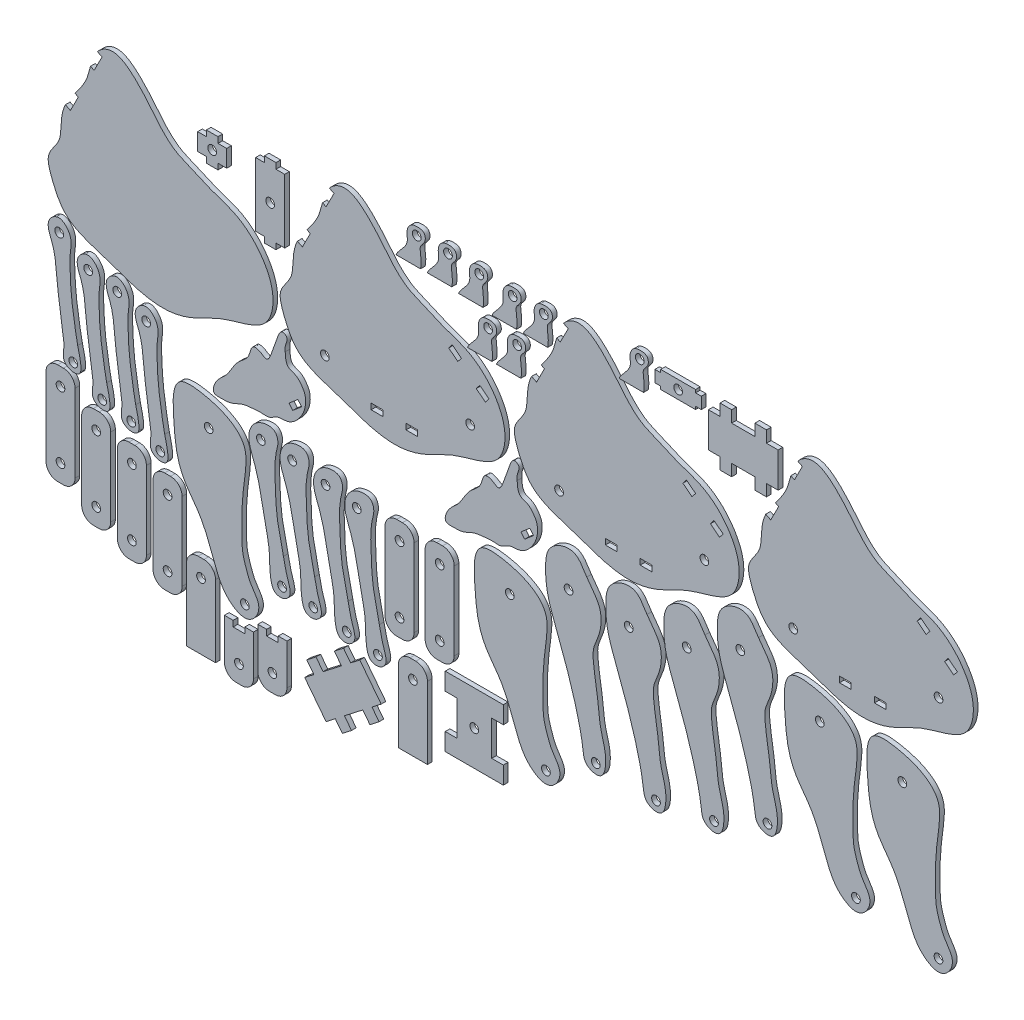
SolidWorks part; units mm, degrees
ref_plane "Front Plane" through (0, 0, 0) normal (0, 0, 1) x (1, 0, 0)
ref_plane "Top Plane" through (0, 0, 0) normal (0, 1, 0) x (1, 0, 0)
ref_plane "Right Plane" through (0, 0, 0) normal (1, 0, 0) x (0, 0, -1)
sketch "Model" plane through (0, 0, 0) normal (0, 0, 1) x (1, 0, 0)
  line L0 (104.0914, 221.0208) -> (99.0726, 224.9111)
  line L1 (99.0726, 224.9111) -> (101.0177, 227.4205)
  line L2 (101.0177, 227.4205) -> (106.0365, 223.5302)
  line L3 (106.0365, 223.5302) -> (104.0914, 221.0208)
  line L4 (116.0741, 215.7496) -> (121.0928, 211.8593)
  line L5 (121.0928, 211.8593) -> (119.1477, 209.3499)
  line L6 (119.1477, 209.3499) -> (114.1289, 213.2402)
  line L7 (114.1289, 213.2402) -> (116.0741, 215.7496)
  line L8 (63.047, 177.6396) -> (56.697, 177.6396)
  line L9 (63.047, 174.4646) -> (63.047, 177.6396)
  line L10 (63.047, 174.4646) -> (56.697, 174.4646)
  line L11 (56.697, 174.4646) -> (56.697, 177.6396)
  line L12 (82.097, 177.6396) -> (75.747, 177.6396)
  line L13 (82.097, 174.4646) -> (82.097, 177.6396)
  line L14 (82.097, 174.4646) -> (75.747, 174.4646)
  line L15 (75.747, 174.4646) -> (75.747, 177.6396)
  line L16 (23.4135, 241.2367) -> (21.6354, 242.1418)
  line L17 (19.0926, 232.7482) -> (23.4135, 241.2367)
  line L18 (19.0926, 232.7482) -> (16.3784, 234.1298)
  line L19 (36.3762, 266.7024) -> (33.8655, 267.9804)
  line L20 (32.0553, 258.2138) -> (36.3762, 266.7024)
  line L21 (32.0553, 258.2138) -> (30.1044, 259.2069)
  line L22 (230.8793, 219.8022) -> (225.8605, 223.6925)
  line L23 (225.8605, 223.6925) -> (227.8057, 226.2019)
  line L24 (227.8057, 226.2019) -> (232.8244, 222.3116)
  line L25 (232.8244, 222.3116) -> (230.8793, 219.8022)
  line L26 (242.862, 214.531) -> (247.8808, 210.6408)
  line L27 (247.8808, 210.6408) -> (245.9356, 208.1314)
  line L28 (245.9356, 208.1314) -> (240.9168, 212.0217)
  line L29 (240.9168, 212.0217) -> (242.862, 214.531)
  line L30 (189.8349, 176.421) -> (183.4849, 176.421)
  line L31 (189.8349, 173.246) -> (189.8349, 176.421)
  line L32 (189.8349, 173.246) -> (183.4849, 173.246)
  line L33 (183.4849, 173.246) -> (183.4849, 176.421)
  line L34 (208.8849, 176.421) -> (202.5349, 176.421)
  line L35 (208.8849, 173.246) -> (208.8849, 176.421)
  line L36 (208.8849, 173.246) -> (202.5349, 173.246)
  line L37 (202.5349, 173.246) -> (202.5349, 176.421)
  line L38 (150.2014, 240.0182) -> (148.4234, 240.9232)
  line L39 (145.8805, 231.5296) -> (150.2014, 240.0182)
  line L40 (145.8805, 231.5296) -> (143.1663, 232.9112)
  line L41 (163.1641, 265.4838) -> (160.6534, 266.7618)
  line L42 (158.8432, 256.9953) -> (163.1641, 265.4838)
  line L43 (158.8432, 256.9953) -> (156.8923, 257.9883)
  line L44 (358.8863, 219.8022) -> (353.8676, 223.6925)
  line L45 (353.8676, 223.6925) -> (355.8127, 226.2019)
  line L46 (355.8127, 226.2019) -> (360.8315, 222.3116)
  line L47 (360.8315, 222.3116) -> (358.8863, 219.8022)
  line L48 (370.869, 214.531) -> (375.8878, 210.6408)
  line L49 (375.8878, 210.6408) -> (373.9427, 208.1314)
  line L50 (373.9427, 208.1314) -> (368.9239, 212.0217)
  line L51 (368.9239, 212.0217) -> (370.869, 214.531)
  line L52 (317.842, 176.421) -> (311.492, 176.421)
  line L53 (317.842, 173.246) -> (317.842, 176.421)
  line L54 (317.842, 173.246) -> (311.492, 173.246)
  line L55 (311.492, 173.246) -> (311.492, 176.421)
  line L56 (336.892, 176.421) -> (330.542, 176.421)
  line L57 (336.892, 173.246) -> (336.892, 176.421)
  line L58 (336.892, 173.246) -> (330.542, 173.246)
  line L59 (330.542, 173.246) -> (330.542, 176.421)
  line L60 (278.2085, 240.0182) -> (276.4304, 240.9232)
  line L61 (273.8876, 231.5296) -> (278.2085, 240.0182)
  line L62 (273.8876, 231.5296) -> (271.1734, 232.9112)
  line L63 (291.1712, 265.4838) -> (288.6604, 266.7618)
  line L64 (286.8503, 256.9953) -> (291.1712, 265.4838)
  line L65 (286.8503, 256.9953) -> (284.8994, 257.9883)
  line L66 (486.8934, 218.5837) -> (481.8746, 222.474)
  line L67 (481.8746, 222.474) -> (483.8198, 224.9833)
  line L68 (483.8198, 224.9833) -> (488.8385, 221.0931)
  line L69 (488.8385, 221.0931) -> (486.8934, 218.5837)
  line L70 (498.8761, 213.3125) -> (503.8949, 209.4222)
  line L71 (503.8949, 209.4222) -> (501.9497, 206.9128)
  line L72 (501.9497, 206.9128) -> (496.9309, 210.8031)
  line L73 (496.9309, 210.8031) -> (498.8761, 213.3125)
  line L74 (445.849, 175.2024) -> (439.499, 175.2024)
  line L75 (445.849, 172.0274) -> (445.849, 175.2024)
  line L76 (445.849, 172.0274) -> (439.499, 172.0274)
  line L77 (439.499, 172.0274) -> (439.499, 175.2024)
  line L78 (464.899, 175.2024) -> (458.549, 175.2024)
  line L79 (464.899, 172.0274) -> (464.899, 175.2024)
  line L80 (464.899, 172.0274) -> (458.549, 172.0274)
  line L81 (458.549, 172.0274) -> (458.549, 175.2024)
  line L82 (406.2155, 238.7996) -> (404.4375, 239.7046)
  line L83 (401.8946, 230.311) -> (406.2155, 238.7996)
  line L84 (401.8946, 230.311) -> (399.1804, 231.6926)
  line L85 (419.1782, 264.2652) -> (416.6675, 265.5432)
  line L86 (414.8573, 255.7767) -> (419.1782, 264.2652)
  line L87 (414.8573, 255.7767) -> (412.9064, 256.7697)
  line L88 (393.2253, 240.0541) -> (399.5753, 240.0541)
  line L89 (399.5753, 246.4041) -> (399.5753, 240.0541)
  line L90 (405.9253, 246.4041) -> (399.5753, 246.4041)
  line L91 (405.9253, 265.4541) -> (405.9253, 246.4041)
  line L92 (399.5753, 265.4541) -> (405.9253, 265.4541)
  line L93 (399.5753, 271.8041) -> (399.5753, 265.4541)
  line L94 (393.2253, 271.8041) -> (399.5753, 271.8041)
  line L95 (393.2253, 265.4541) -> (393.2253, 271.8041)
  line L96 (380.5253, 265.4541) -> (393.2253, 265.4541)
  line L97 (380.5253, 271.8041) -> (380.5253, 265.4541)
  line L98 (374.1753, 271.8041) -> (380.5253, 271.8041)
  line L99 (374.1753, 265.4541) -> (374.1753, 271.8041)
  line L100 (367.8253, 265.4541) -> (374.1753, 265.4541)
  line L101 (367.8253, 265.4541) -> (367.8253, 246.4041)
  line L102 (374.1753, 246.4041) -> (367.8253, 246.4041)
  line L103 (374.1753, 240.0541) -> (374.1753, 246.4041)
  line L104 (374.1753, 240.0541) -> (380.5253, 240.0541)
  line L105 (380.5253, 246.4041) -> (380.5253, 240.0541)
  line L106 (393.2253, 246.4041) -> (380.5253, 246.4041)
  line L107 (393.2253, 240.0541) -> (393.2253, 246.4041)
  line L108 (140.6345, 151.5366) -> (145.4631, 155.6606)
  line L109 (140.6345, 151.5366) -> (138.5725, 153.9509)
  line L110 (138.5725, 153.9509) -> (143.4011, 158.0749)
  line L111 (145.4631, 155.6606) -> (143.4011, 158.0749)
  line L112 (267.4224, 153.9738) -> (272.251, 158.0978)
  line L113 (267.4224, 153.9738) -> (265.3604, 156.3881)
  line L114 (265.3604, 156.3881) -> (270.189, 160.5121)
  line L115 (272.251, 158.0978) -> (270.189, 160.5121)
  line L116 (341.7415, 269.9261) -> (338.5665, 269.9261)
  line L117 (338.5665, 269.9261) -> (338.5665, 263.5761)
  line L118 (341.7415, 263.5761) -> (338.5665, 263.5761)
  line L119 (341.7415, 261.9886) -> (341.7415, 263.5761)
  line L120 (360.7915, 261.9886) -> (341.7415, 261.9886)
  line L121 (360.7915, 261.9886) -> (360.7915, 263.5761)
  line L122 (360.7915, 263.5761) -> (363.9665, 263.5761)
  line L123 (363.9665, 263.5761) -> (363.9665, 269.9261)
  line L124 (360.7915, 269.9261) -> (363.9665, 269.9261)
  line L125 (360.7915, 269.9261) -> (360.7915, 271.5136)
  line L126 (360.7915, 271.5136) -> (341.7415, 271.5136)
  line L127 (341.7415, 269.9261) -> (341.7415, 271.5136)
  line L128 (197.1492, 253.4585) -> (210.4597, 253.4585)
  line L129 (214.2168, 253.4585) -> (227.5273, 253.4585)
  line L130 (231.2844, 252.2399) -> (244.5949, 252.2399)
  line L131 (249.5712, 251.0213) -> (262.8816, 251.0213)
  line L132 (266.6388, 251.0213) -> (279.9492, 251.0213)
  line L133 (252.0094, 229.0869) -> (265.3199, 229.0869)
  line L134 (236.1609, 229.0869) -> (249.4714, 229.0869)
  line L135 (319.0607, 255.8957) -> (332.3712, 255.8957)
  line L136 (120.345, 226.169) -> (120.345, 261.094)
  line L137 (125.1075, 226.169) -> (120.345, 226.169)
  line L138 (125.1075, 226.169) -> (125.1075, 222.994)
  line L139 (125.1075, 222.994) -> (131.4575, 222.994)
  line L140 (131.4575, 226.169) -> (131.4575, 222.994)
  line L141 (136.22, 226.169) -> (131.4575, 226.169)
  line L142 (136.22, 226.169) -> (136.22, 261.094)
  line L143 (136.22, 261.094) -> (131.4575, 261.094)
  line L144 (131.4575, 261.094) -> (131.4575, 264.269)
  line L145 (125.1075, 264.269) -> (131.4575, 264.269)
  line L146 (125.1075, 261.094) -> (125.1075, 264.269)
  line L147 (125.1075, 261.094) -> (120.345, 261.094)
  line L148 (12.0982, 53.6112) -> (15.2732, 53.6112)
  line L149 (21.6232, 59.9612) -> (21.6232, 102.5062)
  line L150 (15.2732, 108.8562) -> (12.0982, 108.8562)
  line L151 (5.7482, 102.5062) -> (5.7482, 59.9612)
  line L152 (31.604, 42.6439) -> (34.779, 42.6439)
  line L153 (41.129, 48.9939) -> (41.129, 91.5389)
  line L154 (34.779, 97.8889) -> (31.604, 97.8889)
  line L155 (25.254, 91.5389) -> (25.254, 48.9939)
  line L156 (51.1099, 36.551) -> (54.2849, 36.551)
  line L157 (60.6349, 42.901) -> (60.6349, 85.446)
  line L158 (54.2849, 91.796) -> (51.1099, 91.796)
  line L159 (44.7599, 85.446) -> (44.7599, 42.901)
  line L160 (70.6157, 31.6767) -> (73.7907, 31.6767)
  line L161 (80.1407, 38.0267) -> (80.1407, 80.5717)
  line L162 (73.7907, 86.9217) -> (70.6157, 86.9217)
  line L163 (64.2657, 80.5717) -> (64.2657, 38.0267)
  line L164 (197.4036, 73.1085) -> (200.5786, 73.1085)
  line L165 (206.9286, 79.4585) -> (206.9286, 122.0035)
  line L166 (200.5786, 128.3535) -> (197.4036, 128.3535)
  line L167 (191.0536, 122.0035) -> (191.0536, 79.4585)
  line L168 (219.3477, 73.1085) -> (222.5227, 73.1085)
  line L169 (228.8727, 79.4585) -> (228.8727, 122.0035)
  line L170 (222.5227, 128.3535) -> (219.3477, 128.3535)
  line L171 (212.9977, 122.0035) -> (212.9977, 79.4585)
  line L172 (223.9697, 60.2517) -> (223.9697, 69.7767)
  line L173 (230.3197, 60.2517) -> (223.9697, 60.2517)
  line L174 (230.3197, 41.2017) -> (230.3197, 60.2517)
  line L175 (230.3197, 41.2017) -> (223.9697, 41.2017)
  line L176 (223.9697, 31.6767) -> (223.9697, 41.2017)
  line L177 (223.9697, 31.6767) -> (255.7197, 31.6767)
  line L178 (255.7197, 31.6767) -> (255.7197, 41.2017)
  line L179 (249.3697, 41.2017) -> (255.7197, 41.2017)
  line L180 (249.3697, 41.2017) -> (249.3697, 60.2517)
  line L181 (249.3697, 60.2517) -> (255.7197, 60.2517)
  line L182 (255.7197, 69.7767) -> (255.7197, 60.2517)
  line L183 (255.7197, 69.7767) -> (223.9697, 69.7767)
  line L184 (82.5524, 10.9608) -> (82.5524, 50.3308)
  line L185 (82.5524, 10.9608) -> (98.4274, 10.9608)
  line L186 (98.4274, 10.9608) -> (98.4274, 50.3308)
  line L187 (88.9024, 56.6808) -> (92.0774, 56.6808)
  line L188 (198.3683, 20.7095) -> (198.3683, 60.0795)
  line L189 (198.3683, 20.7095) -> (214.2433, 20.7095)
  line L190 (214.2433, 20.7095) -> (214.2433, 60.0795)
  line L191 (204.7183, 66.4295) -> (207.8933, 66.4295)
  line L192 (108.0399, 32.7051) -> (108.0399, 35.8801)
  line L193 (108.0399, 35.8801) -> (103.2774, 35.8801)
  line L194 (103.2774, 35.8801) -> (103.2774, 13.6551)
  line L195 (109.6274, 7.3051) -> (112.8024, 7.3051)
  line L196 (119.1524, 13.6551) -> (119.1524, 35.8801)
  line L197 (119.1524, 35.8801) -> (114.3899, 35.8801)
  line L198 (114.3899, 35.8801) -> (114.3899, 32.7051)
  line L199 (114.3899, 32.7051) -> (108.0399, 32.7051)
  line L200 (126.3266, 37.5794) -> (126.3266, 40.7544)
  line L201 (126.3266, 40.7544) -> (121.5641, 40.7544)
  line L202 (121.5641, 40.7544) -> (121.5641, 18.5294)
  line L203 (127.9141, 12.1794) -> (131.0891, 12.1794)
  line L204 (137.4391, 18.5294) -> (137.4391, 40.7544)
  line L205 (137.4391, 40.7544) -> (132.6766, 40.7544)
  line L206 (132.6766, 40.7544) -> (132.6766, 37.5794)
  line L207 (132.6766, 37.5794) -> (126.3266, 37.5794)
  line L208 (88.648, 248.1034) -> (93.4105, 248.1034)
  line L209 (93.4105, 248.1034) -> (93.4105, 244.9284)
  line L210 (93.4105, 244.9284) -> (99.7605, 244.9284)
  line L211 (99.7605, 248.1034) -> (99.7605, 244.9284)
  line L212 (99.7605, 248.1034) -> (104.523, 248.1034)
  line L213 (104.523, 248.1034) -> (104.523, 257.5014)
  line L214 (99.7605, 257.5014) -> (104.523, 257.5014)
  line L215 (99.7605, 257.5014) -> (99.7605, 260.6764)
  line L216 (93.4105, 260.6764) -> (99.7605, 260.6764)
  line L217 (93.4105, 257.5014) -> (93.4105, 260.6764)
  line L218 (88.648, 257.5014) -> (93.4105, 257.5014)
  line L219 (88.648, 248.1034) -> (88.648, 257.5014)
  line L220 (182.8018, 23.8503) -> (187.8206, 27.7406)
  line L221 (183.9303, 32.7594) -> (187.8206, 27.7406)
  line L222 (188.9491, 36.6496) -> (183.9303, 32.7594)
  line L223 (177.2782, 51.706) -> (188.9491, 36.6496)
  line L224 (172.2594, 47.8157) -> (177.2782, 51.706)
  line L225 (168.3691, 52.8345) -> (172.2594, 47.8157)
  line L226 (163.3503, 48.9442) -> (168.3691, 52.8345)
  line L227 (167.2406, 43.9254) -> (163.3503, 48.9442)
  line L228 (157.2031, 36.1448) -> (167.2406, 43.9254)
  line L229 (153.3128, 41.1636) -> (157.2031, 36.1448)
  line L230 (148.294, 37.2733) -> (153.3128, 41.1636)
  line L231 (152.1843, 32.2545) -> (148.294, 37.2733)
  line L232 (147.1655, 28.3642) -> (152.1843, 32.2545)
  line L233 (147.1655, 28.3642) -> (158.8364, 13.3079)
  line L234 (163.8552, 17.1982) -> (158.8364, 13.3079)
  line L235 (167.7455, 12.1794) -> (163.8552, 17.1982)
  line L236 (167.7455, 12.1794) -> (172.7642, 16.0697)
  line L237 (168.8739, 21.0885) -> (172.7642, 16.0697)
  line L238 (178.9115, 28.8691) -> (168.8739, 21.0885)
  line L239 (182.8018, 23.8503) -> (178.9115, 28.8691)
  circle A0 centre (110.8158, 194.5064) radius 2.3813
  circle A1 centre (31.3943, 187.5531) radius 2.3813
  circle A2 centre (237.6038, 193.2878) radius 2.3813
  circle A3 centre (158.1822, 186.3346) radius 2.3813
  circle A4 centre (365.6108, 193.2878) radius 2.3813
  circle A5 centre (286.1892, 186.3346) radius 2.3813
  circle A6 centre (493.6179, 192.0692) radius 2.3813
  circle A7 centre (414.1963, 185.116) radius 2.3813
  circle A8 centre (351.2665, 266.7511) radius 2.3813
  circle A9 centre (306.2513, 67.3847) radius 2.3813
  circle A10 centre (291.3797, 142.1194) radius 2.3813
  circle A11 centre (339.1674, 66.1661) radius 2.3813
  circle A12 centre (324.2958, 140.9008) radius 2.3813
  circle A13 centre (370.8644, 72.259) radius 2.3813
  circle A14 centre (355.9928, 146.9937) radius 2.3813
  circle A15 centre (400.1232, 85.6634) radius 2.3813
  circle A16 centre (385.2515, 160.3981) radius 2.3813
  circle A17 centre (20.6439, 114.275) radius 2.3813
  circle A18 centre (12.9663, 171.868) radius 2.3813
  circle A19 centre (36.4924, 104.5264) radius 2.3813
  circle A20 centre (28.8148, 162.1194) radius 2.3813
  circle A21 centre (52.3409, 102.0892) radius 2.3813
  circle A22 centre (44.6633, 159.6822) radius 2.3813
  circle A23 centre (68.1894, 95.9963) radius 2.3813
  circle A24 centre (60.5118, 153.5893) radius 2.3813
  circle A25 centre (448.4721, 74.6609) radius 2.3813
  circle A26 centre (428.7178, 148.2558) radius 2.3813
  circle A27 centre (493.5793, 68.568) radius 2.3813
  circle A28 centre (473.825, 142.1629) radius 2.3813
  circle A29 centre (279.0151, 50.2893) radius 2.3813
  circle A30 centre (259.2608, 123.8842) radius 2.3813
  circle A31 centre (114.4346, 46.6335) radius 2.3813
  circle A32 centre (94.6803, 120.2284) radius 2.3813
  circle A33 centre (134.774, 65.1672) radius 2.3813
  circle A34 centre (123.1935, 128.8935) radius 2.3813
  circle A35 centre (151.8416, 63.9486) radius 2.3813
  circle A36 centre (140.2611, 127.675) radius 2.3813
  circle A37 centre (170.1283, 61.5115) radius 2.3813
  circle A38 centre (158.5478, 125.2378) radius 2.3813
  circle A39 centre (187.1959, 59.0743) radius 2.3813
  circle A40 centre (175.6154, 122.8006) radius 2.3813
  circle A41 centre (208.3943, 268.1849) radius 2.3813
  circle A42 centre (225.4619, 268.1849) radius 2.3813
  circle A43 centre (242.5295, 266.9664) radius 2.3813
  circle A44 centre (260.8162, 265.7478) radius 2.3813
  circle A45 centre (277.8838, 265.7478) radius 2.3813
  circle A46 centre (263.2544, 243.8133) radius 2.3813
  circle A47 centre (247.406, 243.8133) radius 2.3813
  circle A48 centre (330.3058, 270.6221) radius 2.3813
  circle A49 centre (128.2825, 243.6315) radius 2.3813
  circle A50 centre (13.6857, 63.1362) radius 2.3812
  arc A51 (5.7482, 59.9612) -> (12.0982, 53.6112) centre (12.0982, 59.9612) ccw
  arc A52 (15.2732, 53.6112) -> (21.6232, 59.9612) centre (15.2732, 59.9612) ccw
  arc A53 (21.6232, 102.5062) -> (15.2732, 108.8562) centre (15.2732, 102.5062) ccw
  arc A54 (12.0982, 108.8562) -> (5.7482, 102.5062) centre (12.0982, 102.5062) ccw
  circle A55 centre (13.6857, 99.3312) radius 2.3812
  circle A56 centre (33.1915, 52.1689) radius 2.3813
  arc A57 (25.254, 48.9939) -> (31.604, 42.6439) centre (31.604, 48.9939) ccw
  arc A58 (34.779, 42.6439) -> (41.129, 48.9939) centre (34.779, 48.9939) ccw
  arc A59 (41.129, 91.5389) -> (34.779, 97.8889) centre (34.779, 91.5389) ccw
  arc A60 (31.604, 97.8889) -> (25.254, 91.5389) centre (31.604, 91.5389) ccw
  circle A61 centre (33.1915, 88.3639) radius 2.3813
  circle A62 centre (52.6974, 46.076) radius 2.3813
  arc A63 (44.7599, 42.901) -> (51.1099, 36.551) centre (51.1099, 42.901) ccw
  arc A64 (54.2849, 36.551) -> (60.6349, 42.901) centre (54.2849, 42.901) ccw
  arc A65 (60.6349, 85.446) -> (54.2849, 91.796) centre (54.2849, 85.446) ccw
  arc A66 (51.1099, 91.796) -> (44.7599, 85.446) centre (51.1099, 85.446) ccw
  circle A67 centre (52.6974, 82.271) radius 2.3813
  circle A68 centre (72.2032, 41.2017) radius 2.3813
  arc A69 (64.2657, 38.0267) -> (70.6157, 31.6767) centre (70.6157, 38.0267) ccw
  arc A70 (73.7907, 31.6767) -> (80.1407, 38.0267) centre (73.7907, 38.0267) ccw
  arc A71 (80.1407, 80.5717) -> (73.7907, 86.9217) centre (73.7907, 80.5717) ccw
  arc A72 (70.6157, 86.9217) -> (64.2657, 80.5717) centre (70.6157, 80.5717) ccw
  circle A73 centre (72.2032, 77.3967) radius 2.3813
  circle A74 centre (198.9911, 82.6335) radius 2.3813
  arc A75 (191.0536, 79.4585) -> (197.4036, 73.1085) centre (197.4036, 79.4585) ccw
  arc A76 (200.5786, 73.1085) -> (206.9286, 79.4585) centre (200.5786, 79.4585) ccw
  arc A77 (206.9286, 122.0035) -> (200.5786, 128.3535) centre (200.5786, 122.0035) ccw
  arc A78 (197.4036, 128.3535) -> (191.0536, 122.0035) centre (197.4036, 122.0035) ccw
  circle A79 centre (198.9911, 118.8285) radius 2.3813
  circle A80 centre (220.9352, 82.6335) radius 2.3813
  arc A81 (212.9977, 79.4585) -> (219.3477, 73.1085) centre (219.3477, 79.4585) ccw
  arc A82 (222.5227, 73.1085) -> (228.8727, 79.4585) centre (222.5227, 79.4585) ccw
  arc A83 (228.8727, 122.0035) -> (222.5227, 128.3535) centre (222.5227, 122.0035) ccw
  arc A84 (219.3477, 128.3535) -> (212.9977, 122.0035) centre (219.3477, 122.0035) ccw
  circle A85 centre (220.9352, 118.8285) radius 2.3813
  circle A86 centre (239.8447, 50.7267) radius 2.3813
  circle A87 centre (90.4899, 47.1558) radius 2.3813
  arc A88 (88.9024, 56.6808) -> (82.5524, 50.3308) centre (88.9024, 50.3308) ccw
  arc A89 (98.4274, 50.3308) -> (92.0774, 56.6808) centre (92.0774, 50.3308) ccw
  circle A90 centre (206.3058, 56.9045) radius 2.3813
  arc A91 (204.7183, 66.4295) -> (198.3683, 60.0795) centre (204.7183, 60.0795) ccw
  arc A92 (214.2433, 60.0795) -> (207.8933, 66.4295) centre (207.8933, 60.0795) ccw
  arc A93 (103.2774, 13.6551) -> (109.6274, 7.3051) centre (109.6274, 13.6551) ccw
  arc A94 (112.8024, 7.3051) -> (119.1524, 13.6551) centre (112.8024, 13.6551) ccw
  circle A95 centre (111.2149, 16.8301) radius 2.3813
  arc A96 (121.5641, 18.5294) -> (127.9141, 12.1794) centre (127.9141, 18.5294) ccw
  arc A97 (131.0891, 12.1794) -> (137.4391, 18.5294) centre (131.0891, 18.5294) ccw
  circle A98 centre (129.5016, 21.7044) radius 2.3813
  circle A99 centre (96.5855, 252.8024) radius 2.3813
  spline S0 degree 3 poles (30.1044, 259.2069) (29.4972, 256.9103) (27.9548, 250.5258) (24.0561, 245.3708) (21.6354, 242.1418) knots 0.031107 0.031107 0.031107 0.031107 0.05067 0.084416 0.084416 0.084416 0.084416
  spline S1 degree 3 poles (16.3784, 234.1298) (15.9284, 233.2079) (14.3089, 229.2818) (13.9301, 222.9598) (13.4069, 213.6617) (5.2503, 206.9528) (9.2768, 193.8179) (16.5595, 178.0955) (37.6664, 173.1928) (55.4069, 165.883) (71.7803, 163.4922) (87.3841, 167.8164) (101.0426, 176.2213) (115.1858, 179.0971) (127.2976, 184.9255) (131.7062, 199.673) (125.0562, 216.5503) (111.1645, 229.2923) (96.3678, 233.0741) (86.2086, 238.1772) (73.7041, 242.5383) (64.5153, 254.1951) (54.7221, 265.9313) (43.5965, 274.5023) (36.3939, 270.5676) (34.7542, 268.9588) (34.4359, 268.6465) (34.1406, 268.3199) (33.8655, 267.9804) knots 0.111717 0.111717 0.111717 0.111717 0.120674 0.148904 0.164166 0.198707 0.223619 0.271959 0.340541 0.391818 0.4385 0.47715 0.527178 0.572977 0.600307 0.63604 0.69068 0.746913 0.789386 0.818682 0.843719 0.900659 0.937483 0.980494 1 1 1 1.003787 1.003787 1.003787 1.003787
  spline S2 degree 3 poles (156.8923, 257.9883) (156.2851, 255.6917) (154.7427, 249.3072) (150.844, 244.1522) (148.4234, 240.9232) knots 0.031107 0.031107 0.031107 0.031107 0.05067 0.084416 0.084416 0.084416 0.084416
  spline S3 degree 3 poles (143.1663, 232.9112) (142.7164, 231.9893) (141.0968, 228.0633) (140.718, 221.7412) (140.1948, 212.4431) (132.0382, 205.7342) (136.0647, 192.5994) (143.3475, 176.877) (164.4543, 171.9742) (182.1948, 164.6644) (198.5682, 162.2736) (214.172, 166.5978) (227.8306, 175.0027) (241.9737, 177.8785) (254.0855, 183.707) (258.4942, 198.4544) (251.8441, 215.3318) (237.9524, 228.0737) (223.1557, 231.8556) (212.9966, 236.9586) (200.4921, 241.3197) (191.3032, 252.9765) (181.5101, 264.7127) (170.3844, 273.2838) (163.1818, 269.349) (161.5422, 267.7402) (161.2239, 267.428) (160.9285, 267.1013) (160.6534, 266.7618) knots 0.111717 0.111717 0.111717 0.111717 0.120674 0.148904 0.164166 0.198707 0.223619 0.271959 0.340541 0.391818 0.4385 0.47715 0.527178 0.572977 0.600307 0.63604 0.69068 0.746913 0.789386 0.818682 0.843719 0.900659 0.937483 0.980494 1 1 1 1.003787 1.003787 1.003787 1.003787
  spline S4 degree 3 poles (284.8994, 257.9883) (284.2922, 255.6917) (282.7497, 249.3072) (278.8511, 244.1522) (276.4304, 240.9232) knots 0.031107 0.031107 0.031107 0.031107 0.05067 0.084416 0.084416 0.084416 0.084416
  spline S5 degree 3 poles (271.1734, 232.9112) (270.7234, 231.9893) (269.1038, 228.0633) (268.7251, 221.7412) (268.2018, 212.4431) (260.0453, 205.7342) (264.0718, 192.5994) (271.3545, 176.877) (292.4614, 171.9742) (310.2019, 164.6644) (326.5753, 162.2736) (342.1791, 166.5978) (355.8376, 175.0027) (369.9808, 177.8785) (382.0926, 183.707) (386.5012, 198.4544) (379.8512, 215.3318) (365.9595, 228.0737) (351.1628, 231.8556) (341.0036, 236.9586) (328.4991, 241.3197) (319.3103, 252.9765) (309.5171, 264.7127) (298.3914, 273.2838) (291.1889, 269.349) (289.5492, 267.7402) (289.2309, 267.428) (288.9355, 267.1013) (288.6604, 266.7618) knots 0.111717 0.111717 0.111717 0.111717 0.120674 0.148904 0.164166 0.198707 0.223619 0.271959 0.340541 0.391818 0.4385 0.47715 0.527178 0.572977 0.600307 0.63604 0.69068 0.746913 0.789386 0.818682 0.843719 0.900659 0.937483 0.980494 1 1 1 1.003787 1.003787 1.003787 1.003787
  spline S6 degree 3 poles (412.9064, 256.7697) (412.2992, 254.4731) (410.7568, 248.0886) (406.8581, 242.9336) (404.4375, 239.7046) knots 0.031107 0.031107 0.031107 0.031107 0.05067 0.084416 0.084416 0.084416 0.084416
  spline S7 degree 3 poles (399.1804, 231.6926) (398.7305, 230.7707) (397.1109, 226.8447) (396.7321, 220.5227) (396.2089, 211.2245) (388.0523, 204.5156) (392.0788, 191.3808) (399.3616, 175.6584) (420.4684, 170.7557) (438.2089, 163.4458) (454.5823, 161.0551) (470.1861, 165.3792) (483.8447, 173.7841) (497.9878, 176.6599) (510.0996, 182.4884) (514.5083, 197.2358) (507.8582, 214.1132) (493.9665, 226.8551) (479.1698, 230.637) (469.0107, 235.74) (456.5062, 240.1012) (447.3173, 251.758) (437.5242, 263.4941) (426.3985, 272.0652) (419.1959, 268.1304) (417.5563, 266.5217) (417.238, 266.2094) (416.9426, 265.8827) (416.6675, 265.5432) knots 0.111717 0.111717 0.111717 0.111717 0.120674 0.148904 0.164166 0.198707 0.223619 0.271959 0.340541 0.391818 0.4385 0.47715 0.527178 0.572977 0.600307 0.63604 0.69068 0.746913 0.789386 0.818682 0.843719 0.900659 0.937483 0.980494 1 1 1 1.003787 1.003787 1.003787 1.003787
  spline S8 degree 3 poles (136.5117, 177.2149) (136.454, 178.4223) (136.3411, 180.7138) (138.4378, 184.1882) (133.8902, 187.3014) (132.0494, 180.8342) (130.163, 176.6384) (129.0617, 172.6317) (126.8217, 167.3461) (123.0331, 170.5962) (119.0721, 171.7267) (117.2838, 168.1798) (116.453, 163.5491) (109.0725, 159.3372) (105.6262, 149.9488) (98.6106, 145.8497) (96.6626, 139.347) (97.6453, 138.3486) knots 0.516873 0.516873 0.516873 0.516873 0.538668 0.562806 0.577899 0.616936 0.64534 0.673284 0.701187 0.724121 0.750378 0.764142 0.79167 0.838296 0.910523 0.966354 1 1 1 1
  spline S9 degree 3 poles (97.6453, 138.3486) (98.3895, 137.5924) (102.2917, 137.7586) (107.2513, 137.7035) (112.4035, 140.9433) (118.0574, 141.4301) (122.8359, 142.0592) (127.1765, 141.2541) (130.0493, 143.0401) (133.1494, 144.8295) (138.5998, 144.1057) (144.3788, 149.0441) (147.8568, 155.8093) (147.8246, 162.1931) (145.1705, 166.3246) (142.6063, 169.3739) (136.83, 170.3344) (136.6238, 174.8666) (136.5117, 177.2149) knots 0 0 0 0 0.025479 0.057543 0.099956 0.133034 0.163896 0.19156 0.21193 0.22561 0.258492 0.308276 0.356004 0.401629 0.418999 0.448323 0.474483 0.516873 0.516873 0.516873 0.516873
  spline S10 degree 3 poles (263.2996, 179.6521) (263.242, 180.8594) (263.1291, 183.1509) (265.2258, 186.6254) (260.6781, 189.7386) (258.8373, 183.2714) (256.9509, 179.0756) (255.8497, 175.0689) (253.6096, 169.7832) (249.821, 173.0334) (245.8601, 174.1639) (244.0717, 170.617) (243.241, 165.9863) (235.8605, 161.7744) (232.4141, 152.386) (225.3985, 148.2869) (223.4505, 141.7842) (224.4333, 140.7857) knots 0.516873 0.516873 0.516873 0.516873 0.538668 0.562806 0.577899 0.616936 0.64534 0.673284 0.701187 0.724121 0.750378 0.764142 0.79167 0.838296 0.910523 0.966354 1 1 1 1
  spline S11 degree 3 poles (224.4333, 140.7857) (225.1775, 140.0296) (229.0797, 140.1957) (234.0392, 140.1407) (239.1915, 143.3804) (244.8453, 143.8673) (249.6238, 144.4964) (253.9644, 143.6913) (256.8372, 145.4773) (259.9373, 147.2667) (265.3877, 146.5428) (271.1667, 151.4813) (274.6447, 158.2464) (274.6126, 164.6303) (271.9585, 168.7618) (269.3942, 171.8111) (263.6179, 172.7716) (263.4117, 177.3037) (263.2996, 179.6521) knots 0 0 0 0 0.025479 0.057543 0.099956 0.133034 0.163896 0.19156 0.21193 0.22561 0.258492 0.308276 0.356004 0.401629 0.418999 0.448323 0.474483 0.516873 0.516873 0.516873 0.516873
  spline S12 degree 3 poles (301.3283, 153.0065) (299.2446, 156.1236) (295.1218, 164.447) (279.679, 158.7655) (278.5298, 146.2198) (279.2462, 134.7512) (284.784, 119.6863) (291.2718, 102.9279) (296.4712, 85.2315) (298.7026, 74.861) (299.2635, 70.2267) knots 0.485936 0.485936 0.485936 0.485936 0.533485 0.5968 0.638978 0.694685 0.752921 0.853626 0.938944 1 1 1 1
  spline S13 degree 3 poles (299.2635, 70.2267) (299.5015, 68.2603) (299.9114, 63.4256) (310.2737, 60.2547) (312.1137, 70.3425) (311.0567, 77.8637) (308.3018, 86.4441) (307.5681, 98.5867) (305.2647, 110.0696) (304.348, 121.2467) (309.0851, 129.8911) (310.153, 142.68) (303.8779, 149.1924) (301.3283, 153.0065) knots 0 0 0 0 0.025907 0.061945 0.09921 0.132366 0.170723 0.218452 0.296194 0.330869 0.365118 0.427753 0.485936 0.485936 0.485936 0.485936
  spline S14 degree 3 poles (334.2444, 151.788) (332.1607, 154.9051) (328.0379, 163.2284) (312.5951, 157.5469) (311.4459, 145.0012) (312.1623, 133.5326) (317.7001, 118.4677) (324.1879, 101.7093) (329.3873, 84.0129) (331.6187, 73.6425) (332.1796, 69.0082) knots 0.485936 0.485936 0.485936 0.485936 0.533485 0.5968 0.638978 0.694685 0.752921 0.853626 0.938944 1 1 1 1
  spline S15 degree 3 poles (332.1796, 69.0082) (332.4176, 67.0417) (332.8275, 62.2071) (343.1898, 59.0361) (345.0298, 69.1239) (343.9728, 76.6452) (341.2179, 85.2255) (340.4842, 97.3681) (338.1808, 108.851) (337.2641, 120.0281) (342.0012, 128.6725) (343.0691, 141.4614) (336.794, 147.9738) (334.2444, 151.788) knots 0 0 0 0 0.025907 0.061945 0.09921 0.132366 0.170723 0.218452 0.296194 0.330869 0.365118 0.427753 0.485936 0.485936 0.485936 0.485936
  spline S16 degree 3 poles (365.9414, 157.8809) (363.8577, 160.998) (359.7348, 169.3213) (344.292, 163.6398) (343.1429, 151.0941) (343.8593, 139.6255) (349.3971, 124.5606) (355.8849, 107.8022) (361.0843, 90.1058) (363.3156, 79.7354) (363.8766, 75.1011) knots 0.485936 0.485936 0.485936 0.485936 0.533485 0.5968 0.638978 0.694685 0.752921 0.853626 0.938944 1 1 1 1
  spline S17 degree 3 poles (363.8766, 75.1011) (364.1146, 73.1346) (364.5245, 68.3) (374.8867, 65.129) (376.7268, 75.2168) (375.6698, 82.7381) (372.9149, 91.3184) (372.1812, 103.461) (369.8777, 114.9439) (368.961, 126.121) (373.6981, 134.7654) (374.7661, 147.5543) (368.491, 154.0667) (365.9414, 157.8809) knots 0 0 0 0 0.025907 0.061945 0.09921 0.132366 0.170723 0.218452 0.296194 0.330869 0.365118 0.427753 0.485936 0.485936 0.485936 0.485936
  spline S18 degree 3 poles (395.2001, 171.2853) (393.1164, 174.4024) (388.9936, 182.7257) (373.5508, 177.0442) (372.4016, 164.4985) (373.1181, 153.0299) (378.6559, 137.965) (385.1436, 121.2066) (390.343, 103.5102) (392.5744, 93.1398) (393.1353, 88.5055) knots 0.485936 0.485936 0.485936 0.485936 0.533485 0.5968 0.638978 0.694685 0.752921 0.853626 0.938944 1 1 1 1
  spline S19 degree 3 poles (393.1353, 88.5055) (393.3733, 86.539) (393.7832, 81.7044) (404.1455, 78.5334) (405.9856, 88.6212) (404.9285, 96.1425) (402.1737, 104.7228) (401.4399, 116.8654) (399.1365, 128.3483) (398.2198, 139.5254) (402.9569, 148.1698) (404.0248, 160.9587) (397.7498, 167.4711) (395.2001, 171.2853) knots 0 0 0 0 0.025907 0.061945 0.09921 0.132366 0.170723 0.218452 0.296194 0.330869 0.365118 0.427753 0.485936 0.485936 0.485936 0.485936
  spline S20 degree 3 poles (23.0785, 123.4722) (23.6398, 120.9868) (24.765, 117.0987) (25.2265, 109.1914) (18.1638, 109.4424) (14.6376, 113.4225) (15.9706, 119.0795) (14.885, 125.7187) (13.645, 135.5741) (11.6643, 146.955) (11.1538, 157.7881) (9.6703, 163.617) (9.0122, 165.4003) knots 0.498222 0.498222 0.498222 0.498222 0.550524 0.584938 0.626251 0.649143 0.68416 0.731884 0.784455 0.881469 0.961884 1 1 1 1
  spline S21 degree 3 poles (9.0122, 165.4003) (8.5804, 166.5706) (7.2645, 169.49) (6.1474, 175.4105) (12.457, 180.2233) (17.5561, 176.5328) (20.185, 170.9501) (18.6207, 164.5143) (18.9704, 155.9408) (19.3629, 145.3919) (21.195, 134.0162) (22.432, 126.3344) (23.0785, 123.4722) knots 0 0 0 0 0.025012 0.064561 0.109825 0.141829 0.174905 0.228684 0.267293 0.346435 0.437989 0.498222 0.498222 0.498222 0.498222
  spline S22 degree 3 poles (38.927, 113.7235) (39.4883, 111.2382) (40.6135, 107.3501) (41.075, 99.4427) (34.0123, 99.6938) (30.4861, 103.6739) (31.8191, 109.3309) (30.7335, 115.9701) (29.4935, 125.8254) (27.5128, 137.2063) (27.0023, 148.0395) (25.5188, 153.8684) (24.8607, 155.6517) knots 0.498222 0.498222 0.498222 0.498222 0.550524 0.584938 0.626251 0.649143 0.68416 0.731884 0.784455 0.881469 0.961884 1 1 1 1
  spline S23 degree 3 poles (24.8607, 155.6517) (24.4289, 156.822) (23.113, 159.7413) (21.9959, 165.6619) (28.3055, 170.4746) (33.4046, 166.7842) (36.0335, 161.2015) (34.4692, 154.7657) (34.8188, 146.1922) (35.2114, 135.6433) (37.0435, 124.2676) (38.2805, 116.5857) (38.927, 113.7235) knots 0 0 0 0 0.025012 0.064561 0.109825 0.141829 0.174905 0.228684 0.267293 0.346435 0.437989 0.498222 0.498222 0.498222 0.498222
  spline S24 degree 3 poles (54.7755, 111.2864) (55.3368, 108.801) (56.462, 104.9129) (56.9235, 97.0056) (49.8608, 97.2566) (46.3346, 101.2367) (47.6676, 106.8937) (46.5819, 113.5329) (45.342, 123.3883) (43.3613, 134.7692) (42.8508, 145.6023) (41.3673, 151.4312) (40.7092, 153.2145) knots 0.498222 0.498222 0.498222 0.498222 0.550524 0.584938 0.626251 0.649143 0.68416 0.731884 0.784455 0.881469 0.961884 1 1 1 1
  spline S25 degree 3 poles (40.7092, 153.2145) (40.2774, 154.3848) (38.9615, 157.3042) (37.8444, 163.2247) (44.154, 168.0375) (49.253, 164.347) (51.8819, 158.7643) (50.3176, 152.3285) (50.6673, 143.755) (51.0599, 133.2061) (52.892, 121.8304) (54.129, 114.1486) (54.7755, 111.2864) knots 0 0 0 0 0.025012 0.064561 0.109825 0.141829 0.174905 0.228684 0.267293 0.346435 0.437989 0.498222 0.498222 0.498222 0.498222
  spline S26 degree 3 poles (70.624, 105.1934) (71.1853, 102.7081) (72.3105, 98.82) (72.772, 90.9127) (65.7093, 91.1637) (62.1831, 95.1438) (63.5161, 100.8008) (62.4304, 107.44) (61.1905, 117.2954) (59.2098, 128.6763) (58.6993, 139.5094) (57.2158, 145.3383) (56.5577, 147.1216) knots 0.498222 0.498222 0.498222 0.498222 0.550524 0.584938 0.626251 0.649143 0.68416 0.731884 0.784455 0.881469 0.961884 1 1 1 1
  spline S27 degree 3 poles (56.5577, 147.1216) (56.1259, 148.2919) (54.81, 151.2113) (53.6929, 157.1318) (60.0025, 161.9446) (65.1015, 158.2541) (67.7304, 152.6714) (66.1661, 146.2356) (66.5158, 137.6621) (66.9084, 127.1132) (68.7405, 115.7375) (69.9775, 108.0557) (70.624, 105.1934) knots 0 0 0 0 0.025012 0.064561 0.109825 0.141829 0.174905 0.228684 0.267293 0.346435 0.437989 0.498222 0.498222 0.498222 0.498222
  spline S28 degree 3 poles (454.999, 72.7291) (455.8855, 74.3806) (456.9285, 79.3208) (451.8462, 84.7686) (449.162, 91.9228) (446.7094, 99.4234) (446.9132, 108.5254) (446.5776, 120.527) (448.2841, 133.45) (450.9715, 154.5034) (430.947, 162.9664) (416.0027, 164.0962) (413.3844, 162.5409) knots 0.496265 0.496265 0.496265 0.496265 0.519241 0.556864 0.583624 0.618875 0.657601 0.700502 0.773447 0.830648 0.952544 1 1 1 1
  spline S29 degree 3 poles (413.3844, 162.5409) (408.6133, 159.707) (409.6365, 138.6501) (411.6766, 119.8148) (425.9888, 103.3269) (431.2386, 86.7167) (437.7056, 72.2212) (449.2928, 66.433) (453.9038, 70.6884) (454.999, 72.7291) knots 0 0 0 0 0.086473 0.201224 0.263841 0.35744 0.42531 0.467876 0.496265 0.496265 0.496265 0.496265
  spline S30 degree 3 poles (500.1063, 66.6361) (500.9927, 68.2877) (502.0357, 73.2279) (496.9535, 78.6757) (494.2692, 85.8299) (491.8167, 93.3305) (492.0204, 102.4325) (491.6848, 114.4341) (493.3913, 127.3571) (496.0787, 148.4105) (476.0543, 156.8735) (461.11, 158.0033) (458.4916, 156.448) knots 0.496265 0.496265 0.496265 0.496265 0.519241 0.556864 0.583624 0.618875 0.657601 0.700502 0.773447 0.830648 0.952544 1 1 1 1
  spline S31 degree 3 poles (458.4916, 156.448) (453.7206, 153.6141) (454.7437, 132.5572) (456.7838, 113.7219) (471.096, 97.234) (476.3458, 80.6238) (482.8128, 66.1283) (494.4001, 60.3401) (499.011, 64.5955) (500.1063, 66.6361) knots 0 0 0 0 0.086473 0.201224 0.263841 0.35744 0.42531 0.467876 0.496265 0.496265 0.496265 0.496265
  spline S32 degree 3 poles (285.5421, 48.3574) (286.4285, 50.009) (287.4715, 54.9492) (282.3893, 60.397) (279.705, 67.5512) (277.2525, 75.0518) (277.4562, 84.1538) (277.1206, 96.1553) (278.8271, 109.0784) (281.5145, 130.1318) (261.4901, 138.5948) (246.5458, 139.7246) (243.9274, 138.1693) knots 0.496265 0.496265 0.496265 0.496265 0.519241 0.556864 0.583624 0.618875 0.657601 0.700502 0.773447 0.830648 0.952544 1 1 1 1
  spline S33 degree 3 poles (243.9274, 138.1693) (239.1564, 135.3354) (240.1796, 114.2785) (242.2196, 95.4431) (256.5318, 78.9553) (261.7816, 62.3451) (268.2486, 47.8496) (279.8359, 42.0614) (284.4468, 46.3168) (285.5421, 48.3574) knots 0 0 0 0 0.086473 0.201224 0.263841 0.35744 0.42531 0.467876 0.496265 0.496265 0.496265 0.496265
  spline S34 degree 3 poles (120.9616, 44.7017) (121.848, 46.3533) (122.8911, 51.2935) (117.8088, 56.7413) (115.1245, 63.8954) (112.672, 71.3961) (112.8757, 80.498) (112.5401, 92.4996) (114.2466, 105.4226) (116.934, 126.476) (96.9096, 134.939) (81.9653, 136.0688) (79.3469, 134.5136) knots 0.496265 0.496265 0.496265 0.496265 0.519241 0.556864 0.583624 0.618875 0.657601 0.700502 0.773447 0.830648 0.952544 1 1 1 1
  spline S35 degree 3 poles (79.3469, 134.5136) (74.5759, 131.6797) (75.5991, 110.6227) (77.6392, 91.7874) (91.9513, 75.2996) (97.2012, 58.6894) (103.6681, 44.1938) (115.2554, 38.4056) (119.8663, 42.661) (120.9616, 44.7017) knots 0 0 0 0 0.086473 0.201224 0.263841 0.35744 0.42531 0.467876 0.496265 0.496265 0.496265 0.496265
  spline S36 degree 3 poles (135.5272, 79.9034) (134.4104, 85.2626) (131.5813, 95.922) (130.9978, 112.01) (130.5212, 124.4941) (133.012, 132.317) (131.1125, 137.9194) (124.1581, 138.0154) (118.732, 134.6974) (115.1204, 126.0756) (118.3348, 119.7154) (119.9533, 115.2189) knots 0.478419 0.478419 0.478419 0.478419 0.573139 0.669709 0.758273 0.787002 0.811421 0.84774 0.886903 0.9186 1 1 1 1
  spline S37 degree 3 poles (119.9533, 115.2189) (120.7577, 112.9839) (123.1086, 104.7543) (124.8504, 92.7484) (128.5106, 78.3557) (127.5494, 68.6353) (130.1466, 59.8044) (136.217, 59.2319) (139.7766, 63.2509) (138.7019, 68.1415) (136.7947, 73.3208) (136.0248, 77.5157) (135.5272, 79.9034) knots 0 0 0 0 0.04046 0.15033 0.210445 0.295315 0.324277 0.354468 0.380869 0.404776 0.43622 0.478419 0.478419 0.478419 0.478419
  spline S38 degree 3 poles (152.5948, 78.6848) (151.478, 84.044) (148.6489, 94.7034) (148.0654, 110.7914) (147.5889, 123.2755) (150.0796, 131.0984) (148.1801, 136.7008) (141.2258, 136.7969) (135.7996, 133.4788) (132.188, 124.857) (135.4024, 118.4968) (137.0209, 114.0003) knots 0.478419 0.478419 0.478419 0.478419 0.573139 0.669709 0.758273 0.787002 0.811421 0.84774 0.886903 0.9186 1 1 1 1
  spline S39 degree 3 poles (137.0209, 114.0003) (137.8253, 111.7653) (140.1762, 103.5358) (141.918, 91.5298) (145.5782, 77.1371) (144.617, 67.4167) (147.2142, 58.5859) (153.2846, 58.0133) (156.8442, 62.0324) (155.7695, 66.9229) (153.8623, 72.1022) (153.0924, 76.2971) (152.5948, 78.6848) knots 0 0 0 0 0.04046 0.15033 0.210445 0.295315 0.324277 0.354468 0.380869 0.404776 0.43622 0.478419 0.478419 0.478419 0.478419
  spline S40 degree 3 poles (170.8816, 76.2476) (169.7647, 81.6069) (166.9356, 92.2662) (166.3522, 108.3542) (165.8756, 120.8383) (168.3664, 128.6613) (166.4668, 134.2636) (159.5125, 134.3597) (154.0863, 131.0416) (150.4747, 122.4198) (153.6891, 116.0596) (155.3076, 111.5631) knots 0.478419 0.478419 0.478419 0.478419 0.573139 0.669709 0.758273 0.787002 0.811421 0.84774 0.886903 0.9186 1 1 1 1
  spline S41 degree 3 poles (155.3076, 111.5631) (156.1121, 109.3281) (158.4629, 101.0986) (160.2048, 89.0926) (163.8649, 74.6999) (162.9037, 64.9796) (165.5009, 56.1487) (171.5713, 55.5762) (175.131, 59.5952) (174.0562, 64.4858) (172.149, 69.665) (171.3791, 73.8599) (170.8816, 76.2476) knots 0 0 0 0 0.04046 0.15033 0.210445 0.295315 0.324277 0.354468 0.380869 0.404776 0.43622 0.478419 0.478419 0.478419 0.478419
  spline S42 degree 3 poles (187.9492, 73.8104) (186.8324, 79.1697) (184.0032, 89.8291) (183.4198, 105.9171) (182.9432, 118.4012) (185.434, 126.2241) (183.5344, 131.8265) (176.5801, 131.9225) (171.1539, 128.6045) (167.5423, 119.9827) (170.7568, 113.6224) (172.3752, 109.1259) knots 0.478419 0.478419 0.478419 0.478419 0.573139 0.669709 0.758273 0.787002 0.811421 0.84774 0.886903 0.9186 1 1 1 1
  spline S43 degree 3 poles (172.3752, 109.1259) (173.1797, 106.891) (175.5305, 98.6614) (177.2724, 86.6555) (180.9325, 72.2628) (179.9713, 62.5424) (182.5685, 53.7115) (188.6389, 53.139) (192.1986, 57.158) (191.1238, 62.0486) (189.2166, 67.2279) (188.4467, 71.4228) (187.9492, 73.8104) knots 0 0 0 0 0.04046 0.15033 0.210445 0.295315 0.324277 0.354468 0.380869 0.404776 0.43622 0.478419 0.478419 0.478419 0.478419
  spline S44 degree 3 poles (197.1492, 253.4585) (198.2211, 256.5657) (204.7443, 260.5674) (202.376, 267.7256) (204.8006, 271.9538) (208.5824, 272.6699) (213.0021, 272.2108) (213.4696, 266.9517) (209.8988, 264.6161) (210.7445, 259.3323) (211.0147, 255.9888) (210.4597, 253.4585) knots 0 0 0 0 0.237102 0.355085 0.44147 0.511004 0.597826 0.684225 0.771372 0.837925 1 1 1 1
  spline S45 degree 3 poles (214.2168, 253.4585) (215.2887, 256.5657) (221.8119, 260.5674) (219.4436, 267.7256) (221.8682, 271.9538) (225.65, 272.6699) (230.0697, 272.2108) (230.5372, 266.9517) (226.9664, 264.6161) (227.8121, 259.3323) (228.0823, 255.9888) (227.5273, 253.4585) knots 0 0 0 0 0.237102 0.355085 0.44147 0.511004 0.597826 0.684225 0.771372 0.837925 1 1 1 1
  spline S46 degree 3 poles (231.2844, 252.2399) (232.3564, 255.3471) (238.8795, 259.3488) (236.5112, 266.507) (238.9358, 270.7352) (242.7176, 271.4513) (247.1373, 270.9923) (247.6048, 265.7332) (244.034, 263.3975) (244.8798, 258.1137) (245.1499, 254.7702) (244.5949, 252.2399) knots 0 0 0 0 0.237102 0.355085 0.44147 0.511004 0.597826 0.684225 0.771372 0.837925 1 1 1 1
  spline S47 degree 3 poles (249.5712, 251.0213) (250.6431, 254.1285) (257.1662, 258.1302) (254.7979, 265.2884) (257.2226, 269.5166) (261.0043, 270.2328) (265.424, 269.7737) (265.8915, 264.5146) (262.3207, 262.1789) (263.1665, 256.8951) (263.4367, 253.5517) (262.8816, 251.0213) knots 0 0 0 0 0.237102 0.355085 0.44147 0.511004 0.597826 0.684225 0.771372 0.837925 1 1 1 1
  spline S48 degree 3 poles (266.6388, 251.0213) (267.7107, 254.1285) (274.2338, 258.1302) (271.8655, 265.2884) (274.2902, 269.5166) (278.0719, 270.2328) (282.4916, 269.7737) (282.9591, 264.5146) (279.3883, 262.1789) (280.2341, 256.8951) (280.5043, 253.5517) (279.9492, 251.0213) knots 0 0 0 0 0.237102 0.355085 0.44147 0.511004 0.597826 0.684225 0.771372 0.837925 1 1 1 1
  spline S49 degree 3 poles (252.0094, 229.0869) (253.0813, 232.1941) (259.6045, 236.1958) (257.2361, 243.3539) (259.6608, 247.5821) (263.4425, 248.2983) (267.8622, 247.8392) (268.3298, 242.5801) (264.7589, 240.2445) (265.6047, 234.9607) (265.8749, 231.6172) (265.3199, 229.0869) knots 0 0 0 0 0.237102 0.355085 0.44147 0.511004 0.597826 0.684225 0.771372 0.837925 1 1 1 1
  spline S50 degree 3 poles (236.1609, 229.0869) (237.2328, 232.1941) (243.756, 236.1958) (241.3876, 243.3539) (243.8123, 247.5821) (247.5941, 248.2983) (252.0137, 247.8392) (252.4813, 242.5801) (248.9104, 240.2445) (249.7562, 234.9607) (250.0264, 231.6172) (249.4714, 229.0869) knots 0 0 0 0 0.237102 0.355085 0.44147 0.511004 0.597826 0.684225 0.771372 0.837925 1 1 1 1
  spline S51 degree 3 poles (319.0607, 255.8957) (320.1326, 259.0028) (326.6558, 263.0045) (324.2874, 270.1627) (326.7121, 274.3909) (330.4939, 275.1071) (334.9136, 274.648) (335.3811, 269.3889) (331.8102, 267.0533) (332.656, 261.7695) (332.9262, 258.426) (332.3712, 255.8957) knots 0 0 0 0 0.237102 0.355085 0.44147 0.511004 0.597826 0.684225 0.771372 0.837925 1 1 1 1
extrude "Boss-Extrude1" add sketch "Model" along normal blind 2.54 contours L219 L208 L209 L210 L211 L212 L213 L214 L215 L216 L217 L218 A99 | L146 L147 L136 L137 L138 L139 L140 L141 L142 L143 L144 L145 A49 | L40 S3 L41 L42 L43 S2 L38 L39 L36 L37 L34 L35 L32 L33 L30 L31 L28 L29 L26 L27 L24 L25 L22 L23 A2 A3 | S44 L128 A41 | S45 L129 A42 | S46 L130 A43 | S47 L131 A44 | S48 L132 A45 | S49 L133 A46 | S50 L134 A47 | L62 S5 L63 L64 L65 S4 L60 L61 L58 L59 L56 L57 L54 L55 L52 L53 L50 L51 L48 L49 L46 L47 L44 L45 A4 A5 | S10 S11 L115 L112 L113 L114 | S8 S9 L111 L108 L109 L110 | S51 L135 A48 | L127 L116 L117 L118 L119 L120 L121 L122 L123 L124 L125 L126 A8 | L107 L88 L89 L90 L91 L92 L93 L94 L95 L96 L97 L98 L99 L100 L101 L102 L103 L104 L105 L106 | L84 S7 L85 L86 L87 S6 L82 L83 L80 L81 L78 L79 L76 L77 L74 L75 L72 L73 L70 L71 L68 L69 L66 L67 A6 A7 | S30 S31 A27 A28 | S28 S29 A25 A26 | S18 S19 A15 A16 | S16 S17 A13 A14 | S14 S15 A11 A12 | S12 S13 A9 A10 | S32 S33 A29 A30 | L182 L183 L172 L173 L174 L175 L176 L177 L178 L179 L180 L181 A86 | L190 A92 L191 A91 L188 L189 A90 | L170 A84 L171 A81 L168 A82 L169 A83 A85 A80 | L166 A78 L167 A75 L164 A76 L165 A77 A79 A74 | S42 S43 A39 A40 | S40 S41 A37 A38 | L239 L220 L221 L222 L223 L224 L225 L226 L227 L228 L229 L230 L231 L232 L233 L234 L235 L236 L237 L238 | S38 S39 A35 A36 | S36 S37 A33 A34 | S34 S35 A31 A32 | L203 A97 L204 L205 L206 L207 L200 L201 L202 A96 A98 | L195 A94 L196 L197 L198 L199 L192 L193 L194 A93 A95 | L186 A89 L187 A88 L184 L185 A87 | L162 A72 L163 A69 L160 A70 L161 A71 A73 A68 | L158 A66 L159 A63 L156 A64 L157 A65 A67 A62 | L154 A60 L155 A57 L152 A58 L153 A59 A61 A56 | L150 A54 L151 A51 L148 A52 L149 A53 A55 A50 | S27 S26 A23 A24 | S25 S24 A22 A21 | S23 S22 A19 A20 | S21 S20 A18 A17 | S1 L19 L20 L21 S0 L16 L17 L18
